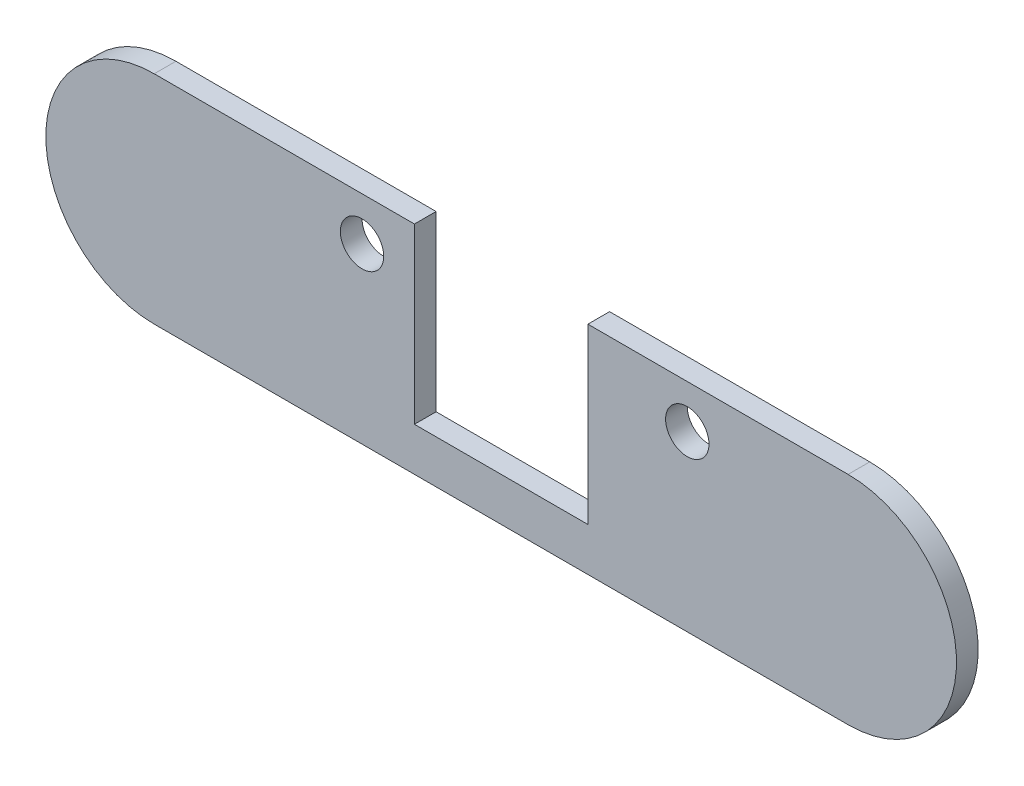
SolidWorks part; units mm, degrees
ref_plane "Plan de face" through (0, 0, 0) normal (0, 0, 1) x (1, 0, 0)
ref_plane "Plan de dessus" through (0, 0, 0) normal (0, 1, 0) x (1, 0, 0)
ref_plane "Plan de droite" through (0, 0, 0) normal (1, 0, 0) x (0, 0, -1)
sketch "Esquisse1" plane through (0, 0, 0) normal (0, 0, 1) x (1, 0, 0)
  line L0 (0, 0) -> (160, 0) construction
  line L1 (0, 25) -> (160, 25)
  line L2 (0, -25) -> (160, -25)
  arc A0 (0, 25) -> (0, -25) centre (0, 0) ccw
  arc A1 (160, -25) -> (160, 25) centre (160, 0) ccw
  circle A2 centre (122.919, 15) radius 5
  circle A3 centre (47.919, 15) radius 5
  point P3 (80, 0)
  dimension "D2" = 25
  dimension "D4" = 10
  dimension "D5" = 10
  dimension "D1" = 160
  dimension "D3" = 75
  dimension "D6" = 40
  dimension "D7" = 10
  dimension "D8" = 10
extrude "Boss.-Extru.1" add sketch "Esquisse1" along normal blind 5
sketch "Esquisse2" plane through (0, 0, 5) normal (0, 0, 1) x (1, 0, 0)
  line L0 (60, 25) -> (60, -15)
  line L1 (160, 25) -> (0, 25) construction
  line L2 (60, -15) -> (100, -15)
  line L3 (100, -15) -> (100, 25)
  line L4 (100, 25) -> (60, 25)
  arc A0 (0, 25) -> (0, -25) centre (0, 0) ccw construction
  dimension "D1" = 40
  dimension "D2" = 40
  dimension "D3" = 60
extrude "Enlèv. mat.-Extru.1" cut sketch "Esquisse2" against normal blind 5
